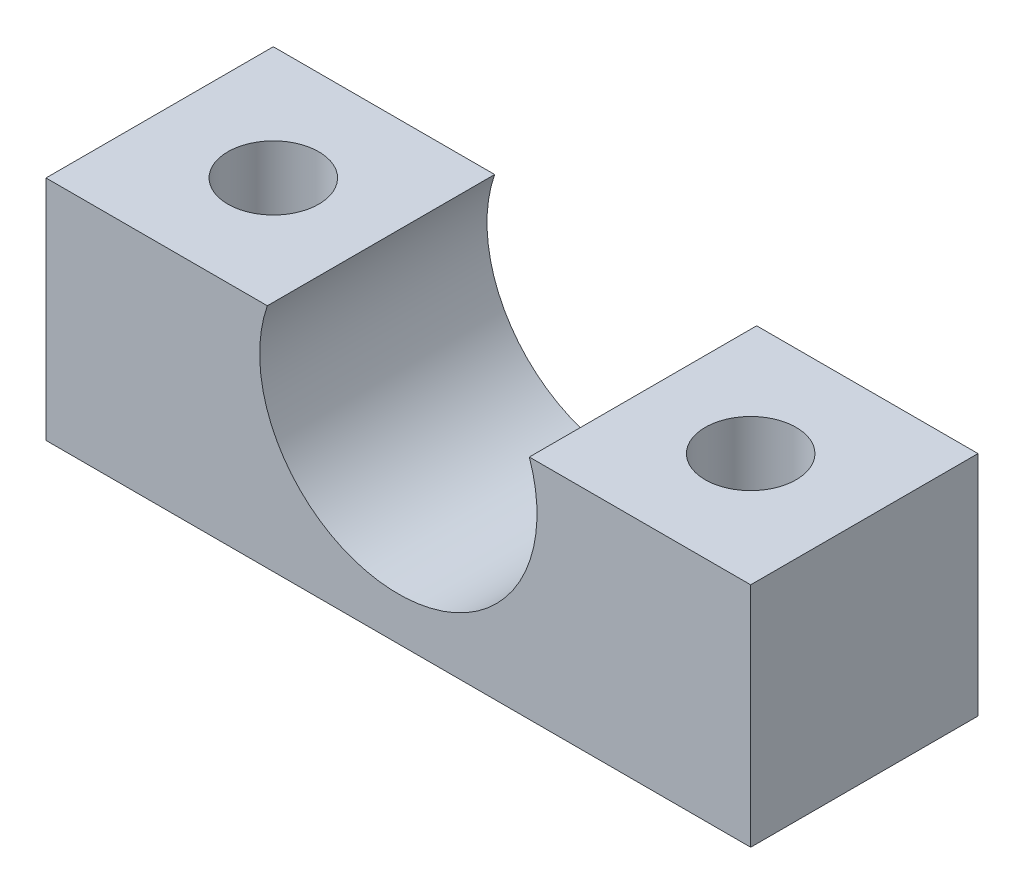
SolidWorks part; units mm, degrees
material "6061 合金"
ref_plane "正面" through (0, 0, 0) normal (0, 0, 1) x (1, 0, 0)
ref_plane "平面" through (0, 0, 0) normal (0, 1, 0) x (1, 0, 0)
ref_plane "右側面" through (0, 0, 0) normal (1, 0, 0) x (0, 0, -1)
sketch "ｽｹｯﾁ1" plane through (0, 0, 0) normal (0, 0, 1) x (1, 0, 0)
  circle A0 centre (0, 0) radius 15
  dimension "D1" = 30
extrude "ﾎﾞｽ - 押し出し1" add sketch "ｽｹｯﾁ1" along normal blind 10
sketch "ｽｹｯﾁ2" plane through (0, 0, 10) normal (0, 0, 1) x (1, 0, 0)
  line L0 (5.7628, 2) -> (20.1459, 2)
  line L1 (-19.8541, 2) -> (-5.7628, 2)
  line L2 (-19.8541, 2) -> (-19.8541, 26.7489)
  line L3 (-19.8541, 26.7489) -> (20.1459, 26.7489)
  line L4 (20.1459, 2) -> (20.1459, 26.7489)
  arc A0 (-5.7628, 2) -> (5.7628, 2) centre (0, 0) ccw
  point P3 (0, 6.1)
  dimension "D1" = 12.2
  dimension "D2" = 40
  dimension "D3" = 2
extrude "ｶｯﾄ - 押し出し1" cut sketch "ｽｹｯﾁ2" against normal blind 10
sketch "ｽｹｯﾁ5" plane through (0, 2, 0) normal (0, 1, 0) x (1, 0, 0)
  line L0 (-14.8661, -5) -> (14.8661, -5) construction
  line L1 (-14.8661, -10) -> (-14.8661, 0) construction
  line L2 (14.8661, 0) -> (14.8661, -10) construction
  line L3 (0, 0) -> (0, -10) construction
  line L4 (6.1, 0) -> (-6.1, 0) construction
  line L5 (-6.1, -10) -> (6.1, -10) construction
  circle A0 centre (-10.5, -5) radius 2
  circle A1 centre (10.5, -5) radius 2
  dimension "D1" = 21
  dimension "D2" = 4
extrude "ｶｯﾄ - 押し出し2" cut sketch "ｽｹｯﾁ5" against normal through all
sketch "ｽｹｯﾁ7" plane through (0, 0, 10) normal (0, 0, 1) x (1, 0, 0)
  line L0 (0, 0) -> (0, -50000) construction
  line L1 (5.7628, 2) -> (14.8661, 2) construction
  line L2 (-15.3243, -18.6888) -> (15.3243, -18.6888)
  line L3 (-15.3243, -18.6888) -> (-15.3243, -8)
  line L4 (-15.3243, -8) -> (15.3243, -8)
  line L5 (15.3243, -18.6888) -> (15.3243, -8)
  line L6 (-15.3243, -18.6888) -> (15.3243, -8) construction
  line L7 (-15.3243, -8) -> (15.3243, -18.6888) construction
  point P3 (0, -13.3444)
  dimension "D1" = 10
extrude "ｶｯﾄ - 押し出し4" cut sketch "ｽｹｯﾁ7" against normal through all
sketch "ｽｹｯﾁ8" plane through (0, 0, 10) normal (0, 0, 1) x (1, 0, 0)
  line L0 (5.7628, 2) -> (14.8661, 2) construction
  line L1 (-15.5, 2) -> (15.5, 2)
  line L2 (-15.5, 2) -> (-15.5, -8)
  line L3 (-15.5, -8) -> (15.5, -8)
  line L4 (15.5, 2) -> (15.5, -8)
  line L5 (0, 0) -> (0, -50000) construction
  line L6 (12.6886, -8) -> (-12.6886, -8) construction
  arc A0 (-5.7628, 2) -> (5.7628, 2) centre (0, 0) ccw construction
  arc A1 (-5.7628, 2) -> (5.7628, 2) centre (0, 0) ccw
  arc M5 (12.6886, -8) -> (14.8661, 2) centre (0, 0) ccw
  arc M9 (-14.8661, 2) -> (-12.6886, -8) centre (0, 0) ccw
  dimension "D1" = 31
extrude "ﾎﾞｽ - 押し出し2" add sketch "ｽｹｯﾁ8" against normal up to surface (10 mm away) contours L2 L3 M9 | L4 L3 M5
